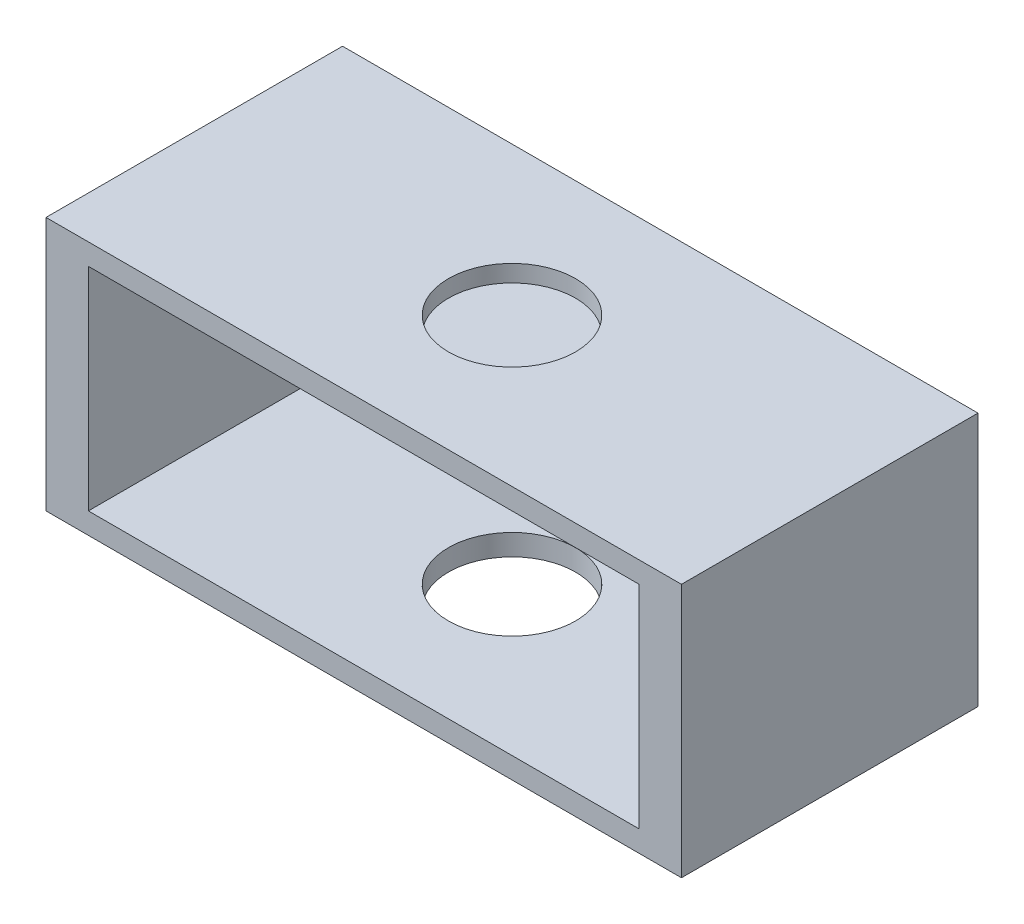
SolidWorks part; units mm, degrees
ref_plane "Спереди" through (0, 0, 0) normal (0, 0, 1) x (1, 0, 0)
ref_plane "Сверху" through (0, 0, 0) normal (0, 1, 0) x (1, 0, 0)
ref_plane "Справа" through (0, 0, 0) normal (1, 0, 0) x (0, 0, -1)
sketch "Эскиз1" plane through (0, 0, 0) normal (0, 1, 0) x (1, 0, 0)
  line L1 (-15, -7) -> (15, -7)
  line L2 (-15, -7) -> (-15, 7)
  line L3 (-15, 7) -> (15, 7)
  line L4 (15, -7) -> (15, 7)
  line L5 (-15, -7) -> (15, 7) construction
  line L6 (-15, 7) -> (15, -7) construction
  circle A0 centre (0, 0) radius 3
  point P0 (0, 0)
  dimension "D3" = 6
  dimension "D1" = 30
  dimension "D2" = 14
extrude "Бобышка-Вытянуть1" add sketch "Эскиз1" along normal blind 1
sketch "Эскиз2" plane through (0, 1, 0) normal (0, 1, 0) x (1, 0, 0)
  line L0 (-1000, 0) -> (49000, 0) construction
  line L1 (0, -1000) -> (0, 49000) construction
  line L2 (-15, 7) -> (-15, -7) construction
  line L3 (-15, 7) -> (-15, -7)
  line L4 (13, 7) -> (15, -7) construction
  line L5 (-13, -7) -> (-15, -7)
  line L6 (-13, -7) -> (-13, 7)
  line L7 (-13, 7) -> (-15, 7)
  line L8 (-15, -7) -> (-15, 7)
  line L9 (-13, -7) -> (-15, 7) construction
  line L10 (-13, 7) -> (-15, -7) construction
  line L11 (13, -7) -> (15, 7) construction
  line L12 (15, -7) -> (15, 7)
  line L13 (13, 7) -> (15, 7)
  line L14 (13, -7) -> (13, 7)
  line L15 (13, -7) -> (15, -7)
  line L16 (15, 7) -> (15, -7)
  point P7 (-14, 0)
  point P15 (14, 0)
  line M6 (15, -7) -> (15, 7)
  line M7 (15, 7) -> (-15, 7)
  line M8 (-15, 7) -> (-15, -7)
  line M9 (-15, -7) -> (15, -7)
  dimension "D1" = 2
extrude "Бобышка-Вытянуть2" add sketch "Эскиз2" along normal blind 10 contours L6 M9 M7 M8 | L14 M9 M6 M7
sketch "Эскиз3" plane through (0, 11, 0) normal (0, 1, 0) x (1, 0, 0)
  line L1 (-15, -7) -> (15, -7)
  line L2 (-15, -7) -> (-15, 7)
  line L3 (-15, 7) -> (15, 7)
  line L4 (15, -7) -> (15, 7)
  line L5 (-15, -7) -> (15, 7) construction
  line L6 (-15, 7) -> (15, -7) construction
  circle A0 centre (0, 0) radius 3
  point P0 (0, 0)
  dimension "D1" = 6
extrude "Бобышка-Вытянуть3" add sketch "Эскиз3" along normal blind 1
sketch "Эскиз4" plane through (0, 11, 0) normal (0, -1, 0) x (1, 0, 0)
  circle A0 centre (0, 0) radius 3
extrude "Бобышка-Вытянуть4" add sketch "Эскиз4" against normal blind 0.2
